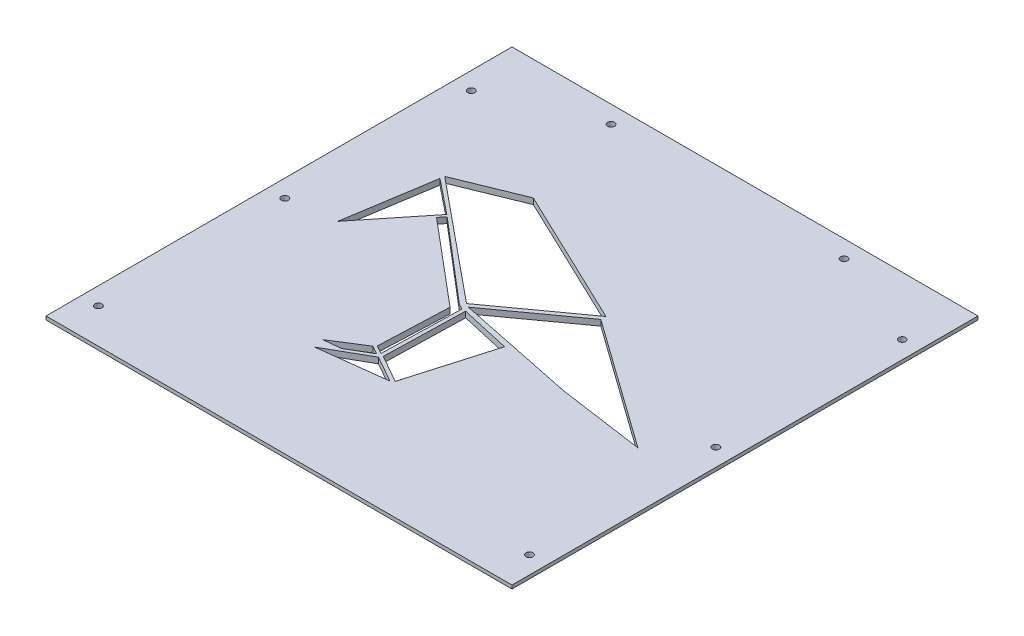
SolidWorks part; units mm, degrees
ref_plane "Alzado" through (0, 0, 0) normal (0, 0, 1) x (1, 0, 0)
ref_plane "Planta" through (0, 0, 0) normal (0, 1, 0) x (1, 0, 0)
ref_plane "Vista lateral" through (0, 0, 0) normal (1, 0, 0) x (0, 0, -1)
sketch "Croquis1" plane through (0, 0, 0) normal (0, 1, 0) x (1, 0, 0)
  line L1 (-188.3268, 170.428) -> (211.6732, 170.428)
  line L2 (-188.3268, 170.428) -> (-188.3268, -229.572)
  line L3 (-188.3268, -229.572) -> (211.6732, -229.572)
  line L4 (211.6732, 170.428) -> (211.6732, -229.572)
  circle A0 centre (-173.3268, 120.428) radius 3
  circle A1 centre (-173.3268, -199.572) radius 3
  circle A2 centre (196.6732, -199.572) radius 3
  circle A3 centre (196.6732, 120.428) radius 3
  circle A4 centre (-173.3268, -39.572) radius 3
  circle A5 centre (196.6732, -39.572) radius 3
  circle A6 centre (-88.3268, 155.428) radius 3
  circle A7 centre (111.6732, 155.428) radius 3
  dimension "D3" = 6
  dimension "D4" = 6
  dimension "D5" = 6
  dimension "D6" = 6
  dimension "D7" = 6
  dimension "D8" = 6
  dimension "D14" = 6
  dimension "D15" = 6
  dimension "D1" = 400
  dimension "D2" = 400
  dimension "D9" = 50
  dimension "D10" = 30
  dimension "D11" = 160
  dimension "D12" = 15
  dimension "D13" = 15
  dimension "D16" = 100
  dimension "D17" = 100
  dimension "D18" = 15
extrude "Saliente-Extruir1" add sketch "Croquis1" along normal blind 5
chamfer "Chaflán1" distance 2 angle 45 4 edges at (-188.3268, 0, 29.572) (11.6732, 0, 229.572) (211.6732, 0, 29.572) (11.6732, 0, -170.428)
sketch "Croquis2" plane through (0, 5, 0) normal (0, 1, 0) x (1, 0, 0)
  line L0 (20.5071, 1076.5625) -> (1897.4294, 1076.5625) construction
  line L1 (-91.7775, 17.9396) -> (-133.4864, -34.0971)
  line L2 (-133.4864, -34.0971) -> (-121.4993, 41.7625)
  line L3 (-120.9404, 45.2999) -> (-66.9663, 67.346)
  line L4 (-66.9663, 67.346) -> (52.3541, 10.3882)
  line L5 (52.3541, 10.3882) -> (-17.0915, -39.8577)
  line L7 (163.7752, -73.5934) -> (52.3541, 6.0091)
  line L8 (163.7752, -73.5934) -> (89.0909, -62.957)
  line L9 (89.0909, -62.957) -> (-13.6044, -41.7248)
  line L10 (31.3118, -55.6605) -> (10.1695, -128.3586)
  line L11 (7.6464, -130.3626) -> (-49.9893, -137.4021)
  line L12 (-49.9893, -137.4021) -> (-15.0038, -117.4529)
  line L13 (-13.5589, -114.8344) -> (-11.8352, -45.8821)
  line L14 (-94.0059, 11.3162) -> (-21.4212, -49.6543)
  line L15 (-21.4212, -49.6543) -> (-23.8688, -109.6196)
  line L16 (-25.5723, -111.6975) -> (-51.9316, -128.3586)
  line L17 (-51.9316, -128.3586) -> (-37.171, -126.8493)
  line L18 (-13.5589, -114.8344) -> (10.1695, -128.3586)
  line L19 (-15.0038, -117.4529) -> (7.6464, -130.3626)
  line L20 (-19.7954, -43.3156) -> (-15.0038, -45.8821)
  line L21 (-120.9404, 45.2999) -> (-17.0915, -39.8577)
  line L22 (52.3541, 6.0091) -> (-13.6044, -41.7248)
  line L23 (-121.4993, 41.7625) -> (-91.7775, 17.9396)
  line L24 (-89.8326, 16.2845) -> (-19.7954, -43.3156)
  line L25 (-89.8326, 16.2845) -> (-94.0059, 11.3162)
  line L26 (-11.8352, -45.8821) -> (31.3118, -55.6605)
  line L27 (-15.0038, -45.8821) -> (-16.6979, -113.6507)
  line L28 (-18.3235, -115.7724) -> (-37.171, -126.8493)
  line L29 (-25.5723, -111.6975) -> (-18.3235, -115.7724)
  line L30 (-23.8688, -109.6196) -> (-16.6979, -113.6507)
  point P2 (903.4376, 504.8568)
extrude "Cortar-Extruir1" cut sketch "Croquis2" against normal blind 10
